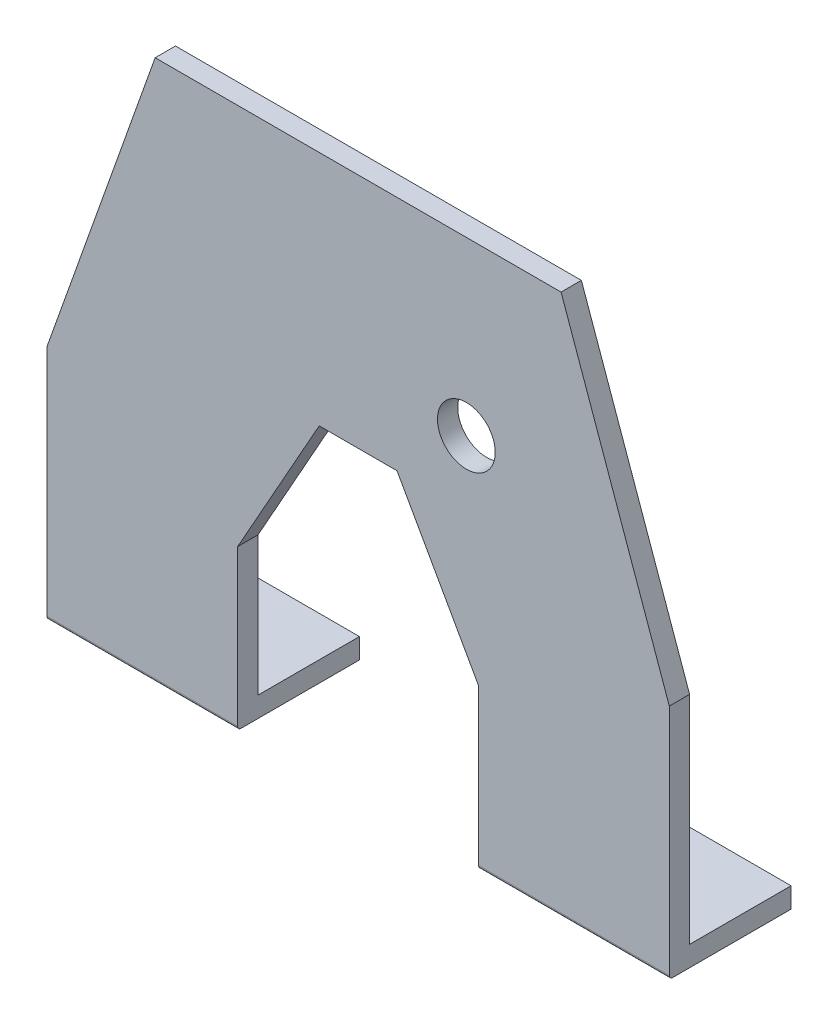
SolidWorks part; units mm, degrees
ref_plane "Alzado" through (0, 0, 0) normal (0, 0, 1) x (1, 0, 0)
ref_plane "Planta" through (0, 0, 0) normal (0, 1, 0) x (1, 0, 0)
ref_plane "Vista lateral" through (0, 0, 0) normal (1, 0, 0) x (0, 0, -1)
sketch "Croquis1" plane through (0, 0, 0) normal (0, 0, 1) x (1, 0, 0)
  line L0 (-46, -40) -> (-46, -5)
  line L1 (46, -40) -> (-46, -40) construction
  line L2 (46, -40) -> (46, 40) construction
  line L3 (46, 40) -> (-46, 40) construction
  line L4 (-46, -40) -> (-46, 40) construction
  line L5 (46, -40) -> (-5.75, 5) construction
  line L6 (46, 40) -> (33.7786, 29.3727) construction
  line L7 (-46, -5) -> (-30, 40)
  line L8 (17.8038, -16.4843) -> (17.8038, -40)
  line L9 (-5.75, 5) -> (5.75, 5)
  line L10 (-17.8038, -16.4843) -> (-17.8038, -40)
  line L11 (-17.8038, -16.4843) -> (-5.75, 5)
  line L12 (0, 0) -> (0, -29.8084) construction
  line L13 (17.8038, -16.4843) -> (5.75, 5)
  line L14 (46, 40) -> (41.4976, 40) construction
  line L15 (46, -40) -> (46, -5)
  line L16 (46, -5) -> (30, 40)
  line L17 (-30, 40) -> (30, 40)
  line L18 (-33.7786, 29.3727) -> (-46, 40) construction
  line L19 (-46, -40) -> (-17.8038, -40)
  line L20 (5.75, 5) -> (-46, -40) construction
  line L21 (17.8038, -40) -> (46, -40)
  circle A0 centre (16, 14.6) radius 4.2718
  point P0 (0, 0)
  point P26 (46, 11.449)
  dimension "D6" = 25.4
  dimension "D1" = 92
  dimension "D2" = 80
  dimension "D3" = 16
  dimension "D4" = 35
  dimension "D5" = 35
  dimension "D7" = 30
extrude "Saliente-Extruir1" add sketch "Croquis1" along normal blind 3
sketch "Croquis2" plane through (0, 0, 0) normal (0, 0, -1) x (-1, 0, 0)
  line L0 (-17.8038, -16.4843) -> (-17.8038, -40) construction
  line L1 (-46, -40) -> (-17.8038, -40)
  line L2 (-46, -40) -> (-46, -37)
  line L3 (-46, -37) -> (-17.8038, -37)
  line L4 (-17.8038, -40) -> (-17.8038, -37)
  line L5 (46, -5) -> (46, -40) construction
  line L6 (17.8038, -40) -> (46, -40)
  line L7 (17.8038, -40) -> (17.8038, -37)
  line L8 (17.8038, -37) -> (46, -37)
  line L9 (46, -40) -> (46, -37)
  dimension "D1" = 3
  dimension "D2" = 3
extrude "Saliente-Extruir2" add sketch "Croquis2" along normal blind 15
fillet "Redondeo1" radius 0.5 2 edges at (-31.9019, -40, 3) (31.9019, -40, 3)
